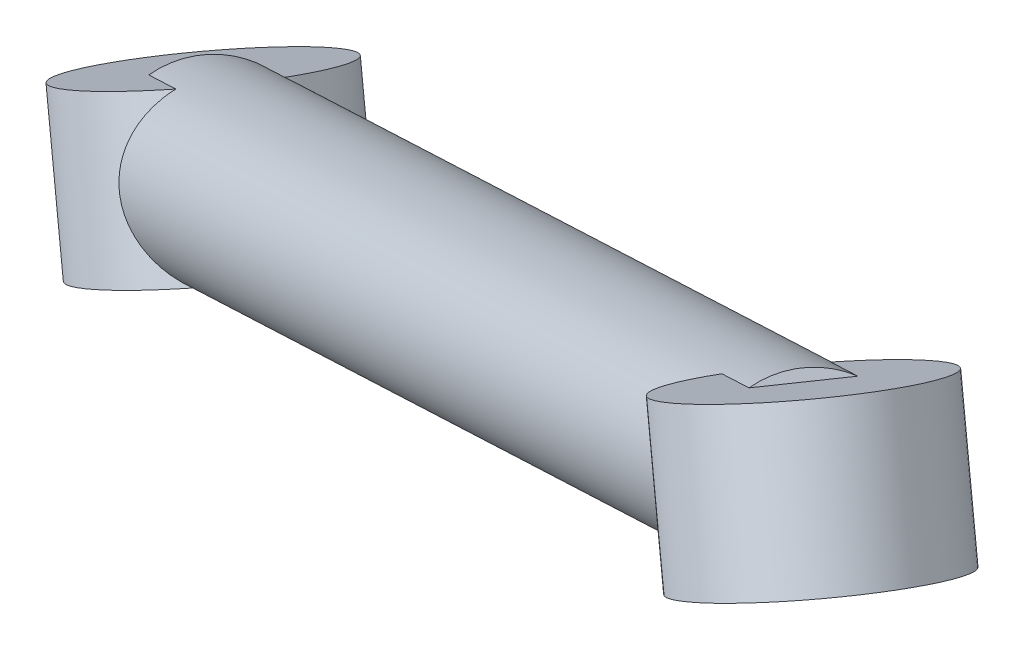
SolidWorks part; units mm, degrees
ref_plane "Plano frontal" through (0, 0, 0) normal (0, 0, 1) x (1, 0, 0)
ref_plane "Plano superior" through (0, 0, 0) normal (0, 1, 0) x (1, 0, 0)
ref_plane "Plano direito" through (0, 0, 0) normal (1, 0, 0) x (0, 0, -1)
sketch3d "SUSP_FL_pullrod_eixo"
  line L0 (-510.46, -91.34, -282.35) -> (-343.0563, 19.7951, -174.0819)
sweep "SUSP_FL_pullrod" add path "SUSP_FL_pullrod_eixo" circular profile diameter 16 parameters "D3"=16
sketch3d "SUSP_FL_pullrod_rod_end_mount_eixo"
  line L0 (-513.2608, -85.2266, -284.2947) -> (-507.6592, -97.4534, -280.4053)
sweep "SUSP_FL_pullrod_rod_end_mount" add path "SUSP_FL_pullrod_rod_end_mount_eixo" circular profile diameter 22 parameters "D3"=22
sketch3d "SUSP_FL_pullrod_rod_end_rocker_eixo"
  line L0 (-345.8571, 25.9085, -176.0266) -> (-340.2555, 13.6817, -172.1372)
sweep "SUSP_FL_pullrod_rod_end_rocker" add path "SUSP_FL_pullrod_rod_end_rocker_eixo" circular profile diameter 22 parameters "D3"=22
sketch3d "REF_SKETCH"
  line L0 (-514.46, -93.74, -284.15) -> (-506.46, -88.94, -280.55)
  line L1 (-508.06, -94.34, -285.55) -> (-512.86, -88.34, -279.15)
  line L2 (-347.0563, 17.3951, -175.8819) -> (-339.0563, 22.1951, -172.2819)
  line L3 (-340.6563, 16.7951, -177.2819) -> (-345.4563, 22.7951, -170.8819)
ref_point "P_MOUNT"
ref_point "P_ROCKER"
